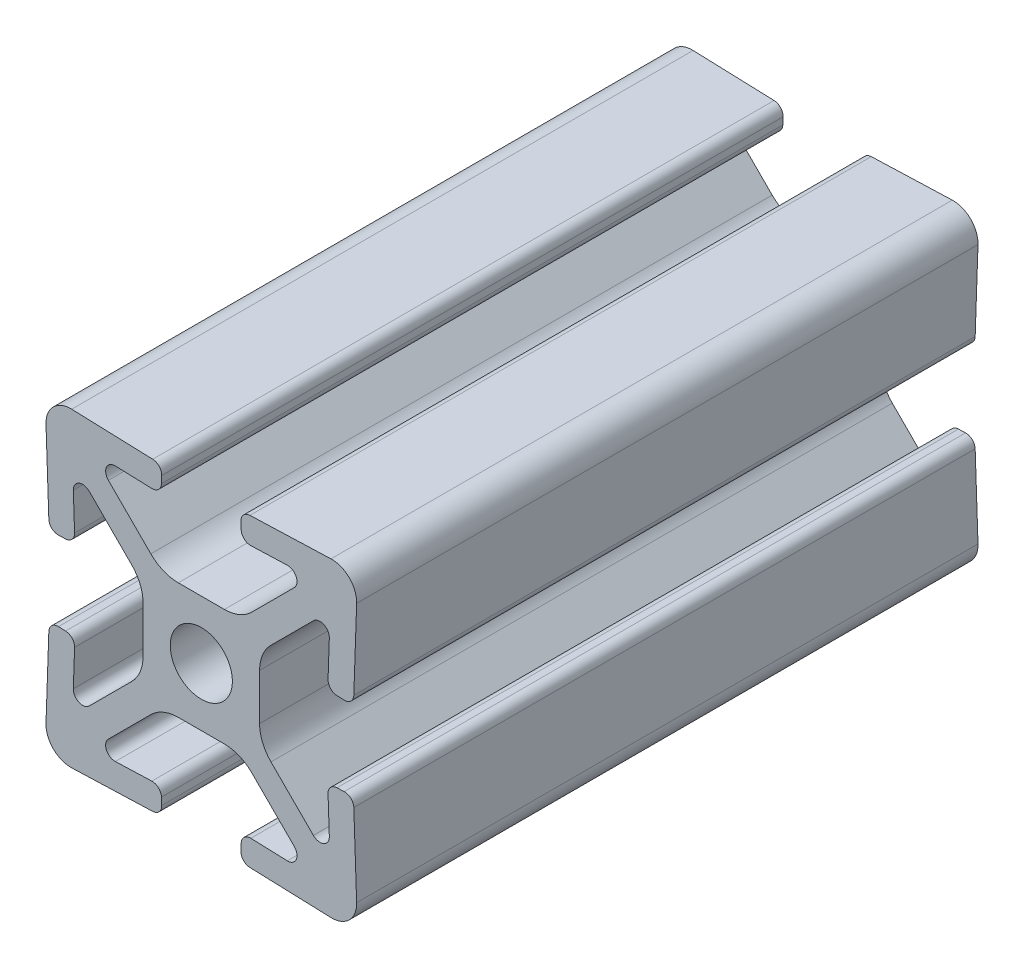
SolidWorks part; units mm, degrees
ref_plane "Front Plane" through (0, 0, 0) normal (0, 0, 1) x (1, 0, 0)
ref_plane "Top Plane" through (0, 0, 0) normal (0, 1, 0) x (1, 0, 0)
ref_plane "Right Plane" through (0, 0, 0) normal (1, 0, 0) x (0, 0, -1)
sketch "Sketch1" plane through (0, 0, 0) normal (0, 0, 1) x (1, 0, 0)
  line L0 (0, 0) -> (0, 12.7) construction
  line L1 (0, 0) -> (12.7, 0) construction
  line L2 (0, 0) -> (-12.7, 12.7) construction
  line L3 (-10.5971, 12.6988) -> (-3.9739, 12.4675)
  line L4 (-12.7, 12.7) -> (0, 12.7) construction
  line L6 (-4.0475, 10.3606) -> (-7.0332, 10.4648)
  line L10 (0, 4.7625) -> (-1.8848, 4.7625)
  line L11 (-4.1299, 5.6924) -> (-7.5996, 9.1622)
  line L24 (0, 0) -> (-12.7, 0) construction
  line L25 (-12.7, 0) -> (0, 0) construction
  line L26 (0, 0) -> (0, -12.7) construction
  line L27 (-12.7, -12.7) -> (-12.7, 12.7) construction
  line L28 (0, 12.7) -> (12.7, 12.7) construction
  line L29 (-3.239, 11.6793) -> (-3.2594, 11.0955)
  line L30 (-12.7, -12.7) -> (12.7, -12.7) construction
  arc A0 (-12.1048, 12.1048) -> (-10.5971, 12.6988) centre (-10.668, 10.668) cw
  arc A6 (-1.8848, 4.7625) -> (-4.1299, 5.6924) centre (-1.8848, 7.9375) cw
  circle A16 centre (0, 0) radius 2.54
  arc A18 (-7.5996, 9.1622) -> (-7.0332, 10.4648) centre (-7.0599, 9.702) cw
  circle A19 centre (-2.3794, 2.3794) radius 0.635 construction
  arc A20 (-4.0475, 10.3606) -> (-3.2594, 11.0955) centre (-4.0209, 11.1221) ccw
  arc A21 (-3.9739, 12.4675) -> (-3.239, 11.6793) centre (-4.0005, 11.7059) cw
  point P15 (0, 0)
  point P42 (-3.1999, 4.7625)
  point P80 (-12.7, 0)
  point P85 (0, -12.7)
  point P88 (0, -12.7)
  dimension "D11" = 2.032
  dimension "D15" = 3.175
  dimension "Center Hole Diameter" = 5.08
  dimension "D6" = 1.27
  dimension "D4" = 0.7633
  dimension "D8" = 0.762
  dimension "D12" = 0.762
  dimension "D1" = 45
  dimension "D2" = 2
  dimension "Rail Width" = 25.4
  dimension "D10" = 2.2098
  dimension "T-Slot Depth" = 7.9375
  dimension "D9" = 2.1082
  dimension "Rail Height" = 25.4
  dimension "D23" = 9.525
  dimension "D5" = 15.6464
  dimension "D3" = 4
  dimension "D7" = 5.7028
  dimension "T-Slot Width" = 6.477
sketch "Sketch2" plane through (0, 0, 0) normal (1, 0, 0) x (0, 0, -1)
  line L0 (-609.6, 0) -> (609.6, 0)
  line L2 (0, 0) -> (0, 12.7) construction
  line L3 (0, 0) -> (0, 12.7) construction
  point P0 (-571.5, 0)
  point P3 (0, 0)
  point P7 (571.5, 0)
  dimension "D1" = 38.1
  dimension "Length" = 1219.2
sketch "Sketch3" plane through (0, 0, 0) normal (0, 0, 1) x (1, 0, 0)
  line L2 (0, 4.7625) -> (-1.8848, 4.7625) construction
  line L5 (-4.1299, 5.6924) -> (-7.5996, 9.1622) construction
  line L6 (-4.0475, 10.3606) -> (-7.0332, 10.4648) construction
  line L7 (-3.239, 11.6793) -> (-3.2594, 11.0955) construction
  line L67 (-10.5971, 12.6988) -> (-3.9739, 12.4675) construction
  line L68 (0, 4.7625) -> (-1.8848, 4.7625)
  line L69 (-4.1299, 5.6924) -> (-7.5996, 9.1622)
  line L70 (-4.0475, 10.3606) -> (-7.0332, 10.4648)
  line L71 (-3.239, 11.6793) -> (-3.2594, 11.0955)
  line L72 (-10.5971, 12.6988) -> (-3.9739, 12.4675)
  line L73 (0, 0) -> (-12.7, 12.7) construction
  line L74 (0, 0) -> (-12.7, 12.7) construction
  line L75 (-12.6988, 10.5971) -> (-12.4675, 3.9739)
  line L76 (-11.6793, 3.239) -> (-11.0955, 3.2594)
  line L77 (-10.3606, 4.0475) -> (-10.4648, 7.0332)
  line L78 (-5.6924, 4.1299) -> (-9.1622, 7.5996)
  line L79 (-4.7625, 0) -> (-4.7625, 1.8848)
  line L80 (-4.7625, 0) -> (-2.54, 0)
  line L82 (0, 4.7625) -> (0, 2.54)
  arc A3 (-4.1299, 5.6924) -> (-1.8848, 4.7625) centre (-1.8848, 7.9375) ccw construction
  circle A10 centre (0, 0) radius 2.54
  arc A56 (0, 2.54) -> (-2.54, 0) centre (0, 0) ccw
  arc A57 (-7.0332, 10.4648) -> (-7.5996, 9.1622) centre (-7.0599, 9.702) ccw construction
  arc A58 (-4.0475, 10.3606) -> (-3.2594, 11.0955) centre (-4.0209, 11.1221) ccw construction
  arc A59 (-3.239, 11.6793) -> (-3.9739, 12.4675) centre (-4.0005, 11.7059) ccw construction
  arc A60 (-10.5971, 12.6988) -> (-12.1048, 12.1048) centre (-10.668, 10.668) ccw construction
  arc A61 (-4.1299, 5.6924) -> (-1.8848, 4.7625) centre (-1.8848, 7.9375) ccw
  arc A62 (-7.0332, 10.4648) -> (-7.5996, 9.1622) centre (-7.0599, 9.702) ccw
  arc A63 (-4.0475, 10.3606) -> (-3.2594, 11.0955) centre (-4.0209, 11.1221) ccw
  arc A64 (-3.239, 11.6793) -> (-3.9739, 12.4675) centre (-4.0005, 11.7059) ccw
  arc A65 (-10.5971, 12.6988) -> (-12.6988, 10.5971) centre (-10.668, 10.668) ccw
  arc A67 (-11.6793, 3.239) -> (-12.4675, 3.9739) centre (-11.7059, 4.0005) cw
  arc A68 (-10.3606, 4.0475) -> (-11.0955, 3.2594) centre (-11.1221, 4.0209) cw
  arc A69 (-10.4648, 7.0332) -> (-9.1622, 7.5996) centre (-9.702, 7.0599) cw
  arc A70 (-5.6924, 4.1299) -> (-4.7625, 1.8848) centre (-7.9375, 1.8848) cw
  dimension "D1" = 0
extrude "Boss-Extrude1" add sketch "Sketch3" along normal mid plane 1219.2
pattern_circular "CirPattern1" count 4 over 360 about axis through (0, 0, 0) along (0, 0, 1) of "Boss-Extrude1"
ref_plane "Contact Plane 1" through (0, 12.7, 0) normal (0, 1, 0) x (1, 0, 0)
ref_plane "Contact Plane 2" through (12.7, 0, 0) normal (1, 0, 0) x (0, 0, -1)
ref_plane "Contact Plane 3" through (0, -12.7, 0) normal (0, -1, 0) x (-1, 0, 0)
ref_plane "Contact Plane 4" through (-12.7, 0, 0) normal (-1, 0, 0) x (0, 0, 1)
sketch "Sketch4" plane through (0, 0, 609.6) normal (0, 0, 1) x (1, 0, 0)
  line L36 (1.8848, 4.7625) -> (-1.8848, 4.7625)
  line L37 (-4.1299, 5.6924) -> (-7.5996, 9.1622)
  line L38 (-7.0332, 10.4648) -> (-4.0475, 10.3606)
  line L39 (-3.2594, 11.0955) -> (-3.239, 11.6793)
  line L40 (-3.9739, 12.4675) -> (-10.5971, 12.6988)
  line L41 (-12.6988, 10.5971) -> (-12.4675, 3.9739)
  line L42 (-11.6793, 3.239) -> (-11.0955, 3.2594)
  line L43 (-10.3606, 4.0475) -> (-10.4648, 7.0332)
  line L44 (-9.1622, 7.5996) -> (-5.6924, 4.1299)
  line L45 (-4.7625, 1.8848) -> (-4.7625, -1.8848)
  line L46 (-5.6924, -4.1299) -> (-9.1622, -7.5996)
  line L47 (-10.4648, -7.0332) -> (-10.3606, -4.0475)
  line L48 (-11.0955, -3.2594) -> (-11.6793, -3.239)
  line L49 (-12.4675, -3.9739) -> (-12.6988, -10.5971)
  line L50 (-10.5971, -12.6988) -> (-3.9739, -12.4675)
  line L51 (-3.239, -11.6793) -> (-3.2594, -11.0955)
  line L52 (-4.0475, -10.3606) -> (-7.0332, -10.4648)
  line L53 (-7.5996, -9.1622) -> (-4.1299, -5.6924)
  line L54 (-1.8848, -4.7625) -> (1.8848, -4.7625)
  line L55 (4.1299, -5.6924) -> (7.5996, -9.1622)
  line L56 (7.0332, -10.4648) -> (4.0475, -10.3606)
  line L57 (3.2594, -11.0955) -> (3.239, -11.6793)
  line L58 (3.9739, -12.4675) -> (10.5971, -12.6988)
  line L59 (12.6988, -10.5971) -> (12.4675, -3.9739)
  line L60 (11.6793, -3.239) -> (11.0955, -3.2594)
  line L61 (10.3606, -4.0475) -> (10.4648, -7.0332)
  line L62 (9.1622, -7.5996) -> (5.6924, -4.1299)
  line L63 (4.7625, -1.8848) -> (4.7625, 1.8848)
  line L64 (5.6924, 4.1299) -> (9.1622, 7.5996)
  line L65 (10.4648, 7.0332) -> (10.3606, 4.0475)
  line L66 (11.0955, 3.2594) -> (11.6793, 3.239)
  line L67 (12.4675, 3.9739) -> (12.6988, 10.5971)
  line L68 (10.5971, 12.6988) -> (3.9739, 12.4675)
  line L69 (3.239, 11.6793) -> (3.2594, 11.0955)
  line L70 (4.0475, 10.3606) -> (7.0332, 10.4648)
  line L71 (7.5996, 9.1622) -> (4.1299, 5.6924)
  line L72 (1.8848, 4.7625) -> (-1.8848, 4.7625)
  line L73 (-4.1299, 5.6924) -> (-7.5996, 9.1622)
  line L74 (-7.0332, 10.4648) -> (-4.0475, 10.3606)
  line L75 (-3.2594, 11.0955) -> (-3.239, 11.6793)
  line L76 (-3.9739, 12.4675) -> (-10.5971, 12.6988)
  line L77 (-12.6988, 10.5971) -> (-12.4675, 3.9739)
  line L78 (-11.6793, 3.239) -> (-11.0955, 3.2594)
  line L79 (-10.3606, 4.0475) -> (-10.4648, 7.0332)
  line L80 (-9.1622, 7.5996) -> (-5.6924, 4.1299)
  line L81 (-4.7625, 1.8848) -> (-4.7625, -1.8848)
  line L82 (-5.6924, -4.1299) -> (-9.1622, -7.5996)
  line L83 (-10.4648, -7.0332) -> (-10.3606, -4.0475)
  line L84 (-11.0955, -3.2594) -> (-11.6793, -3.239)
  line L85 (-12.4675, -3.9739) -> (-12.6988, -10.5971)
  line L86 (-10.5971, -12.6988) -> (-3.9739, -12.4675)
  line L87 (-3.239, -11.6793) -> (-3.2594, -11.0955)
  line L88 (-4.0475, -10.3606) -> (-7.0332, -10.4648)
  line L89 (-7.5996, -9.1622) -> (-4.1299, -5.6924)
  line L90 (-1.8848, -4.7625) -> (1.8848, -4.7625)
  line L91 (4.1299, -5.6924) -> (7.5996, -9.1622)
  line L92 (7.0332, -10.4648) -> (4.0475, -10.3606)
  line L93 (3.2594, -11.0955) -> (3.239, -11.6793)
  line L94 (3.9739, -12.4675) -> (10.5971, -12.6988)
  line L95 (12.6988, -10.5971) -> (12.4675, -3.9739)
  line L96 (11.6793, -3.239) -> (11.0955, -3.2594)
  line L97 (10.3606, -4.0475) -> (10.4648, -7.0332)
  line L98 (9.1622, -7.5996) -> (5.6924, -4.1299)
  line L99 (4.7625, -1.8848) -> (4.7625, 1.8848)
  line L100 (5.6924, 4.1299) -> (9.1622, 7.5996)
  line L101 (10.4648, 7.0332) -> (10.3606, 4.0475)
  line L102 (11.0955, 3.2594) -> (11.6793, 3.239)
  line L103 (12.4675, 3.9739) -> (12.6988, 10.5971)
  line L104 (10.5971, 12.6988) -> (3.9739, 12.4675)
  line L105 (3.239, 11.6793) -> (3.2594, 11.0955)
  line L106 (4.0475, 10.3606) -> (7.0332, 10.4648)
  line L107 (7.5996, 9.1622) -> (4.1299, 5.6924)
  arc A36 (1.8848, 4.7625) -> (4.1299, 5.6924) centre (1.8848, 7.9375) ccw
  arc A37 (-4.1299, 5.6924) -> (-1.8848, 4.7625) centre (-1.8848, 7.9375) ccw
  arc A38 (-7.0332, 10.4648) -> (-7.5996, 9.1622) centre (-7.0599, 9.702) ccw
  arc A39 (-4.0475, 10.3606) -> (-3.2594, 11.0955) centre (-4.0209, 11.1221) ccw
  arc A40 (-3.239, 11.6793) -> (-3.9739, 12.4675) centre (-4.0005, 11.7059) ccw
  arc A41 (-10.5971, 12.6988) -> (-12.6988, 10.5971) centre (-10.668, 10.668) ccw
  arc A42 (-12.4675, 3.9739) -> (-11.6793, 3.239) centre (-11.7059, 4.0005) ccw
  arc A43 (-11.0955, 3.2594) -> (-10.3606, 4.0475) centre (-11.1221, 4.0209) ccw
  arc A44 (-9.1622, 7.5996) -> (-10.4648, 7.0332) centre (-9.702, 7.0599) ccw
  arc A45 (-4.7625, 1.8848) -> (-5.6924, 4.1299) centre (-7.9375, 1.8848) ccw
  arc A46 (-5.6924, -4.1299) -> (-4.7625, -1.8848) centre (-7.9375, -1.8848) ccw
  arc A47 (-10.4648, -7.0332) -> (-9.1622, -7.5996) centre (-9.702, -7.0599) ccw
  arc A48 (-10.3606, -4.0475) -> (-11.0955, -3.2594) centre (-11.1221, -4.0209) ccw
  arc A49 (-11.6793, -3.239) -> (-12.4675, -3.9739) centre (-11.7059, -4.0005) ccw
  arc A50 (-12.6988, -10.5971) -> (-10.5971, -12.6988) centre (-10.668, -10.668) ccw
  arc A51 (-3.9739, -12.4675) -> (-3.239, -11.6793) centre (-4.0005, -11.7059) ccw
  arc A52 (-3.2594, -11.0955) -> (-4.0475, -10.3606) centre (-4.0209, -11.1221) ccw
  arc A53 (-7.5996, -9.1622) -> (-7.0332, -10.4648) centre (-7.0599, -9.702) ccw
  arc A54 (-1.8848, -4.7625) -> (-4.1299, -5.6924) centre (-1.8848, -7.9375) ccw
  arc A55 (4.1299, -5.6924) -> (1.8848, -4.7625) centre (1.8848, -7.9375) ccw
  arc A56 (7.0332, -10.4648) -> (7.5996, -9.1622) centre (7.0599, -9.702) ccw
  arc A57 (4.0475, -10.3606) -> (3.2594, -11.0955) centre (4.0209, -11.1221) ccw
  arc A58 (3.239, -11.6793) -> (3.9739, -12.4675) centre (4.0005, -11.7059) ccw
  arc A59 (10.5971, -12.6988) -> (12.6988, -10.5971) centre (10.668, -10.668) ccw
  arc A60 (12.4675, -3.9739) -> (11.6793, -3.239) centre (11.7059, -4.0005) ccw
  arc A61 (11.0955, -3.2594) -> (10.3606, -4.0475) centre (11.1221, -4.0209) ccw
  arc A62 (9.1622, -7.5996) -> (10.4648, -7.0332) centre (9.702, -7.0599) ccw
  arc A63 (4.7625, -1.8848) -> (5.6924, -4.1299) centre (7.9375, -1.8848) ccw
  arc A64 (5.6924, 4.1299) -> (4.7625, 1.8848) centre (7.9375, 1.8848) ccw
  arc A65 (10.4648, 7.0332) -> (9.1622, 7.5996) centre (9.702, 7.0599) ccw
  arc A66 (10.3606, 4.0475) -> (11.0955, 3.2594) centre (11.1221, 4.0209) ccw
  arc A67 (11.6793, 3.239) -> (12.4675, 3.9739) centre (11.7059, 4.0005) ccw
  arc A68 (12.6988, 10.5971) -> (10.5971, 12.6988) centre (10.668, 10.668) ccw
  arc A69 (3.9739, 12.4675) -> (3.239, 11.6793) centre (4.0005, 11.7059) ccw
  arc A70 (3.2594, 11.0955) -> (4.0475, 10.3606) centre (4.0209, 11.1221) ccw
  arc A71 (7.5996, 9.1622) -> (7.0332, 10.4648) centre (7.0599, 9.702) ccw
  arc A72 (1.8848, 4.7625) -> (4.1299, 5.6924) centre (1.8848, 7.9375) ccw
  arc A73 (-4.1299, 5.6924) -> (-1.8848, 4.7625) centre (-1.8848, 7.9375) ccw
  arc A74 (-7.0332, 10.4648) -> (-7.5996, 9.1622) centre (-7.0599, 9.702) ccw
  arc A75 (-4.0475, 10.3606) -> (-3.2594, 11.0955) centre (-4.0209, 11.1221) ccw
  arc A76 (-3.239, 11.6793) -> (-3.9739, 12.4675) centre (-4.0005, 11.7059) ccw
  arc A77 (-10.5971, 12.6988) -> (-12.6988, 10.5971) centre (-10.668, 10.668) ccw
  arc A78 (-12.4675, 3.9739) -> (-11.6793, 3.239) centre (-11.7059, 4.0005) ccw
  arc A79 (-11.0955, 3.2594) -> (-10.3606, 4.0475) centre (-11.1221, 4.0209) ccw
  arc A80 (-9.1622, 7.5996) -> (-10.4648, 7.0332) centre (-9.702, 7.0599) ccw
  arc A81 (-4.7625, 1.8848) -> (-5.6924, 4.1299) centre (-7.9375, 1.8848) ccw
  arc A82 (-5.6924, -4.1299) -> (-4.7625, -1.8848) centre (-7.9375, -1.8848) ccw
  arc A83 (-10.4648, -7.0332) -> (-9.1622, -7.5996) centre (-9.702, -7.0599) ccw
  arc A84 (-10.3606, -4.0475) -> (-11.0955, -3.2594) centre (-11.1221, -4.0209) ccw
  arc A85 (-11.6793, -3.239) -> (-12.4675, -3.9739) centre (-11.7059, -4.0005) ccw
  arc A86 (-12.6988, -10.5971) -> (-10.5971, -12.6988) centre (-10.668, -10.668) ccw
  arc A87 (-3.9739, -12.4675) -> (-3.239, -11.6793) centre (-4.0005, -11.7059) ccw
  arc A88 (-3.2594, -11.0955) -> (-4.0475, -10.3606) centre (-4.0209, -11.1221) ccw
  arc A89 (-7.5996, -9.1622) -> (-7.0332, -10.4648) centre (-7.0599, -9.702) ccw
  arc A90 (-1.8848, -4.7625) -> (-4.1299, -5.6924) centre (-1.8848, -7.9375) ccw
  arc A91 (4.1299, -5.6924) -> (1.8848, -4.7625) centre (1.8848, -7.9375) ccw
  arc A92 (7.0332, -10.4648) -> (7.5996, -9.1622) centre (7.0599, -9.702) ccw
  arc A93 (4.0475, -10.3606) -> (3.2594, -11.0955) centre (4.0209, -11.1221) ccw
  arc A94 (3.239, -11.6793) -> (3.9739, -12.4675) centre (4.0005, -11.7059) ccw
  arc A95 (10.5971, -12.6988) -> (12.6988, -10.5971) centre (10.668, -10.668) ccw
  arc A96 (12.4675, -3.9739) -> (11.6793, -3.239) centre (11.7059, -4.0005) ccw
  arc A97 (11.0955, -3.2594) -> (10.3606, -4.0475) centre (11.1221, -4.0209) ccw
  arc A98 (9.1622, -7.5996) -> (10.4648, -7.0332) centre (9.702, -7.0599) ccw
  arc A99 (4.7625, -1.8848) -> (5.6924, -4.1299) centre (7.9375, -1.8848) ccw
  arc A100 (5.6924, 4.1299) -> (4.7625, 1.8848) centre (7.9375, 1.8848) ccw
  arc A101 (10.4648, 7.0332) -> (9.1622, 7.5996) centre (9.702, 7.0599) ccw
  arc A102 (10.3606, 4.0475) -> (11.0955, 3.2594) centre (11.1221, 4.0209) ccw
  arc A103 (11.6793, 3.239) -> (12.4675, 3.9739) centre (11.7059, 4.0005) ccw
  arc A104 (12.6988, 10.5971) -> (10.5971, 12.6988) centre (10.668, 10.668) ccw
  arc A105 (3.9739, 12.4675) -> (3.239, 11.6793) centre (4.0005, 11.7059) ccw
  arc A106 (3.2594, 11.0955) -> (4.0475, 10.3606) centre (4.0209, 11.1221) ccw
  arc A107 (7.5996, 9.1622) -> (7.0332, 10.4648) centre (7.0599, 9.702) ccw
  dimension "D1" = 0
extrude "Cut-Extrude1" cut sketch "Sketch4" against normal offset from surface (1168.4 mm away) 50.8
equation "\"D1@Sketch2\"=\"Rail Width@Sketch1\"*1.5"
equation "\"D1@Boss-Extrude1\"=\"Length@Sketch2\""
